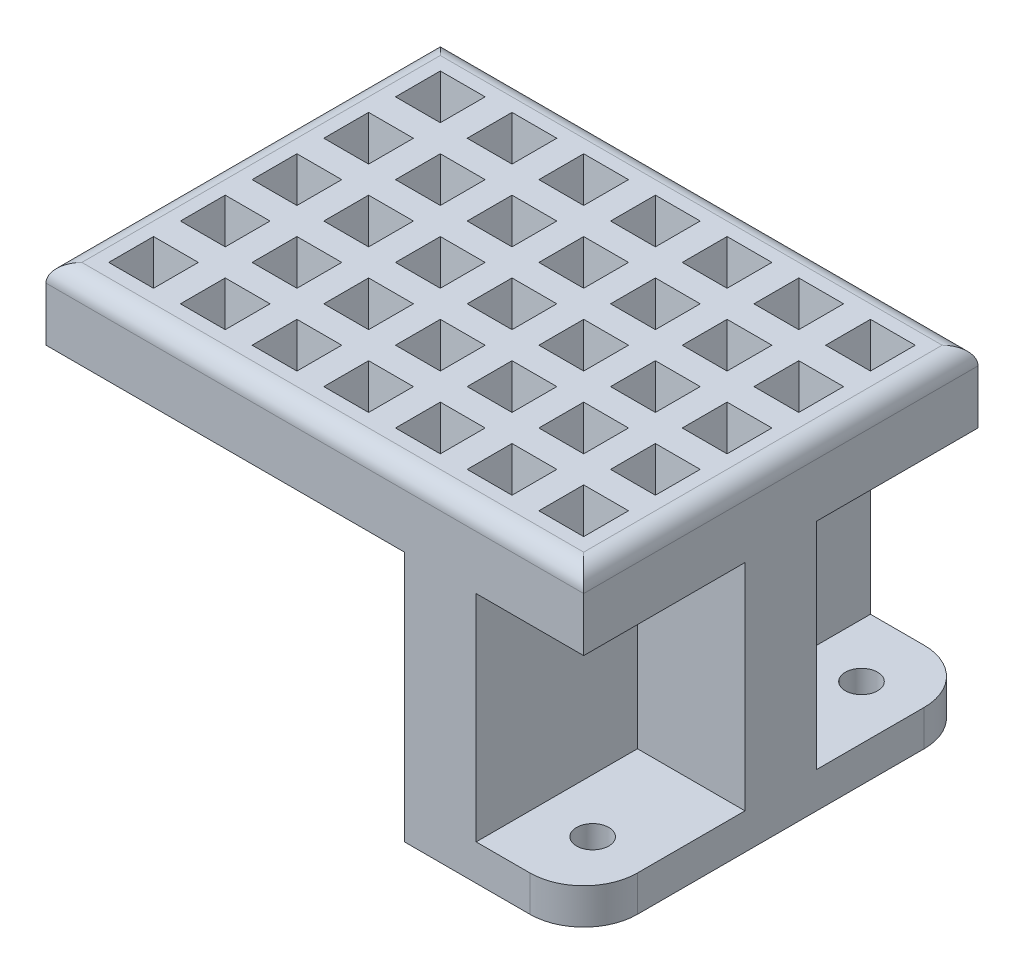
SolidWorks part; units mm, degrees
ref_plane "Спереди" through (0, 0, 0) normal (0, 0, 1) x (1, 0, 0)
ref_plane "Сверху" through (0, 0, 0) normal (0, 1, 0) x (1, 0, 0)
ref_plane "Справа" through (0, 0, 0) normal (1, 0, 0) x (0, 0, -1)
sketch "Эскиз1" plane through (0, 0, 0) normal (0, 1, 0) x (1, 0, 0)
  line L1 (0, -11) -> (-7, -11)
  line L2 (3, -8) -> (3, 8)
  line L3 (0, 11) -> (-7, 11)
  line L4 (-7, -11) -> (-7, 11)
  line L5 (3, -11) -> (-7, 11) construction
  line L6 (3, 11) -> (-7, -11) construction
  circle A0 centre (0, 7.5) radius 0.9
  circle A1 centre (0, -7.5) radius 0.9
  arc A2 (0, -11) -> (3, -8) centre (0, -8) ccw
  arc A3 (3, 8) -> (0, 11) centre (0, 8) ccw
  point P4 (-2, 0)
  dimension "D1" = 1.8
  dimension "D7" = 3
  dimension "D2" = 15
  dimension "D3" = 7.5
  dimension "D4" = 22
  dimension "D5" = 10
  dimension "D6" = 2
extrude "Бобышка-Вытянуть1" add sketch "Эскиз1" along normal blind 2
sketch "Эскиз2" plane through (0, 2, 0) normal (0, 1, 0) x (1, 0, 0)
  line L1 (-3, -11) -> (-7, -11)
  line L2 (-3, -11) -> (-3, -2)
  line L3 (-3, 11) -> (-7, 11)
  line L4 (-7, -11) -> (-7, 11)
  line L5 (-3, -11) -> (-7, 11) construction
  line L6 (-3, 11) -> (-7, -11) construction
  line L7 (-7, 11) -> (-7, -11) construction
  line L8 (-3, 2) -> (-3, 11)
  line L9 (3, -2) -> (-3, -2)
  line L10 (3, -2) -> (3, 2)
  line L11 (3, 2) -> (-3, 2)
  line L13 (3, -2) -> (-3, 2) construction
  line L14 (3, 2) -> (-3, -2) construction
  point P0 (-5, 0)
  point P9 (-7, 0)
  point P10 (0, 0)
  dimension "D1" = 4
  dimension "D2" = 4
extrude "Бобышка-Вытянуть2" add sketch "Эскиз2" along normal blind 12
sketch "Эскиз3" plane through (0, 14, 0) normal (0, 1, 0) x (1, 0, 0)
  line L0 (-7, 11) -> (-7, -11) construction
  line L1 (-27, 11) -> (3, 11)
  line L2 (-27, 11) -> (-27, -11)
  line L3 (-27, -11) -> (3, -11)
  line L4 (3, 11) -> (3, -11)
  line L5 (-27, 11) -> (3, -11) construction
  line L6 (-27, -11) -> (3, 11) construction
  line L8 (3, -2) -> (3, 2) construction
  point P0 (-12, 0)
  point P7 (0, 0)
  point P8 (0, 0)
  dimension "D1" = 30
extrude "Бобышка-Вытянуть3" add sketch "Эскиз3" along normal blind 4
sketch "Эскиз4" plane through (0, 18, 0) normal (0, 1, 0) x (1, 0, 0)
  line L0 (-21.25, 9.25) -> (-21.25, 6.75)
  line L1 (-25.25, 9.25) -> (-22.75, 9.25)
  line L2 (-25.25, 9.25) -> (-25.25, 6.75)
  line L3 (-25.25, 6.75) -> (-22.75, 6.75)
  line L4 (-22.75, 9.25) -> (-22.75, 6.75)
  line L5 (-25.25, 9.25) -> (-22.75, 6.75) construction
  line L6 (-25.25, 6.75) -> (-22.75, 9.25) construction
  line L7 (-21.25, 9.25) -> (-18.75, 9.25)
  line L8 (-18.75, 9.25) -> (-18.75, 6.75)
  line L9 (-21.25, 6.75) -> (-18.75, 6.75)
  line L10 (-17.25, 9.25) -> (-17.25, 6.75)
  line L11 (-17.25, 9.25) -> (-14.75, 9.25)
  line L12 (-14.75, 9.25) -> (-14.75, 6.75)
  line L13 (-17.25, 6.75) -> (-14.75, 6.75)
  line L14 (-13.25, 9.25) -> (-13.25, 6.75)
  line L15 (-13.25, 9.25) -> (-10.75, 9.25)
  line L16 (-10.75, 9.25) -> (-10.75, 6.75)
  line L17 (-13.25, 6.75) -> (-10.75, 6.75)
  line L18 (-9.25, 9.25) -> (-9.25, 6.75)
  line L19 (-9.25, 9.25) -> (-6.75, 9.25)
  line L20 (-6.75, 9.25) -> (-6.75, 6.75)
  line L21 (-9.25, 6.75) -> (-6.75, 6.75)
  line L22 (-5.25, 9.25) -> (-5.25, 6.75)
  line L23 (-5.25, 9.25) -> (-2.75, 9.25)
  line L24 (-2.75, 9.25) -> (-2.75, 6.75)
  line L25 (-5.25, 6.75) -> (-2.75, 6.75)
  line L26 (-1.25, 9.25) -> (-1.25, 6.75)
  line L27 (-1.25, 9.25) -> (1.25, 9.25)
  line L28 (1.25, 9.25) -> (1.25, 6.75)
  line L29 (-1.25, 6.75) -> (1.25, 6.75)
  line L34 (-21.25, 5.25) -> (-21.25, 2.75)
  line L35 (-21.25, 5.25) -> (-18.75, 5.25)
  line L36 (-18.75, 5.25) -> (-18.75, 2.75)
  line L37 (-21.25, 2.75) -> (-18.75, 2.75)
  line L38 (-17.25, 5.25) -> (-17.25, 2.75)
  line L39 (-17.25, 5.25) -> (-14.75, 5.25)
  line L40 (-14.75, 5.25) -> (-14.75, 2.75)
  line L41 (-17.25, 2.75) -> (-14.75, 2.75)
  line L42 (-13.25, 5.25) -> (-13.25, 2.75)
  line L43 (-13.25, 5.25) -> (-10.75, 5.25)
  line L44 (-10.75, 5.25) -> (-10.75, 2.75)
  line L45 (-13.25, 2.75) -> (-10.75, 2.75)
  line L46 (-9.25, 5.25) -> (-9.25, 2.75)
  line L47 (-9.25, 5.25) -> (-6.75, 5.25)
  line L48 (-6.75, 5.25) -> (-6.75, 2.75)
  line L49 (-9.25, 2.75) -> (-6.75, 2.75)
  line L50 (-5.25, 5.25) -> (-5.25, 2.75)
  line L51 (-5.25, 5.25) -> (-2.75, 5.25)
  line L52 (-2.75, 5.25) -> (-2.75, 2.75)
  line L53 (-5.25, 2.75) -> (-2.75, 2.75)
  line L54 (-1.25, 5.25) -> (-1.25, 2.75)
  line L55 (-1.25, 5.25) -> (1.25, 5.25)
  line L56 (1.25, 5.25) -> (1.25, 2.75)
  line L57 (-1.25, 2.75) -> (1.25, 2.75)
  line L62 (-21.25, 1.25) -> (-21.25, -1.25)
  line L63 (-21.25, 1.25) -> (-18.75, 1.25)
  line L64 (-18.75, 1.25) -> (-18.75, -1.25)
  line L65 (-21.25, -1.25) -> (-18.75, -1.25)
  line L66 (-17.25, 1.25) -> (-17.25, -1.25)
  line L67 (-17.25, 1.25) -> (-14.75, 1.25)
  line L68 (-14.75, 1.25) -> (-14.75, -1.25)
  line L69 (-17.25, -1.25) -> (-14.75, -1.25)
  line L70 (-13.25, 1.25) -> (-13.25, -1.25)
  line L71 (-13.25, 1.25) -> (-10.75, 1.25)
  line L72 (-10.75, 1.25) -> (-10.75, -1.25)
  line L73 (-13.25, -1.25) -> (-10.75, -1.25)
  line L74 (-9.25, 1.25) -> (-9.25, -1.25)
  line L75 (-9.25, 1.25) -> (-6.75, 1.25)
  line L76 (-6.75, 1.25) -> (-6.75, -1.25)
  line L77 (-9.25, -1.25) -> (-6.75, -1.25)
  line L78 (-5.25, 1.25) -> (-5.25, -1.25)
  line L79 (-5.25, 1.25) -> (-2.75, 1.25)
  line L80 (-2.75, 1.25) -> (-2.75, -1.25)
  line L81 (-5.25, -1.25) -> (-2.75, -1.25)
  line L82 (-1.25, 1.25) -> (-1.25, -1.25)
  line L83 (-1.25, 1.25) -> (1.25, 1.25)
  line L84 (1.25, 1.25) -> (1.25, -1.25)
  line L85 (-1.25, -1.25) -> (1.25, -1.25)
  line L90 (-21.25, -2.75) -> (-21.25, -5.25)
  line L91 (-21.25, -2.75) -> (-18.75, -2.75)
  line L92 (-18.75, -2.75) -> (-18.75, -5.25)
  line L93 (-21.25, -5.25) -> (-18.75, -5.25)
  line L94 (-17.25, -2.75) -> (-17.25, -5.25)
  line L95 (-17.25, -2.75) -> (-14.75, -2.75)
  line L96 (-14.75, -2.75) -> (-14.75, -5.25)
  line L97 (-17.25, -5.25) -> (-14.75, -5.25)
  line L98 (-13.25, -2.75) -> (-13.25, -5.25)
  line L99 (-13.25, -2.75) -> (-10.75, -2.75)
  line L100 (-10.75, -2.75) -> (-10.75, -5.25)
  line L101 (-13.25, -5.25) -> (-10.75, -5.25)
  line L102 (-9.25, -2.75) -> (-9.25, -5.25)
  line L103 (-9.25, -2.75) -> (-6.75, -2.75)
  line L104 (-6.75, -2.75) -> (-6.75, -5.25)
  line L105 (-9.25, -5.25) -> (-6.75, -5.25)
  line L106 (-5.25, -2.75) -> (-5.25, -5.25)
  line L107 (-5.25, -2.75) -> (-2.75, -2.75)
  line L108 (-2.75, -2.75) -> (-2.75, -5.25)
  line L109 (-5.25, -5.25) -> (-2.75, -5.25)
  line L110 (-1.25, -2.75) -> (-1.25, -5.25)
  line L111 (-1.25, -2.75) -> (1.25, -2.75)
  line L112 (1.25, -2.75) -> (1.25, -5.25)
  line L113 (-1.25, -5.25) -> (1.25, -5.25)
  line L118 (-21.25, -6.75) -> (-21.25, -9.25)
  line L119 (-21.25, -6.75) -> (-18.75, -6.75)
  line L120 (-18.75, -6.75) -> (-18.75, -9.25)
  line L121 (-21.25, -9.25) -> (-18.75, -9.25)
  line L122 (-17.25, -6.75) -> (-17.25, -9.25)
  line L123 (-17.25, -6.75) -> (-14.75, -6.75)
  line L124 (-14.75, -6.75) -> (-14.75, -9.25)
  line L125 (-17.25, -9.25) -> (-14.75, -9.25)
  line L126 (-13.25, -6.75) -> (-13.25, -9.25)
  line L127 (-13.25, -6.75) -> (-10.75, -6.75)
  line L128 (-10.75, -6.75) -> (-10.75, -9.25)
  line L129 (-13.25, -9.25) -> (-10.75, -9.25)
  line L130 (-9.25, -6.75) -> (-9.25, -9.25)
  line L131 (-9.25, -6.75) -> (-6.75, -6.75)
  line L132 (-6.75, -6.75) -> (-6.75, -9.25)
  line L133 (-9.25, -9.25) -> (-6.75, -9.25)
  line L134 (-5.25, -6.75) -> (-5.25, -9.25)
  line L135 (-5.25, -6.75) -> (-2.75, -6.75)
  line L136 (-2.75, -6.75) -> (-2.75, -9.25)
  line L137 (-5.25, -9.25) -> (-2.75, -9.25)
  line L138 (-1.25, -6.75) -> (-1.25, -9.25)
  line L139 (-1.25, -6.75) -> (1.25, -6.75)
  line L140 (1.25, -6.75) -> (1.25, -9.25)
  line L141 (-1.25, -9.25) -> (1.25, -9.25)
  line L146 (-25.25, 5.25) -> (-25.25, 2.75)
  line L147 (-25.25, 5.25) -> (-22.75, 5.25)
  line L148 (-22.75, 5.25) -> (-22.75, 2.75)
  line L149 (-25.25, 2.75) -> (-22.75, 2.75)
  line L150 (-25.25, 1.25) -> (-25.25, -1.25)
  line L151 (-25.25, 1.25) -> (-22.75, 1.25)
  line L152 (-22.75, 1.25) -> (-22.75, -1.25)
  line L153 (-25.25, -1.25) -> (-22.75, -1.25)
  line L154 (-25.25, -2.75) -> (-25.25, -5.25)
  line L155 (-25.25, -2.75) -> (-22.75, -2.75)
  line L156 (-22.75, -2.75) -> (-22.75, -5.25)
  line L157 (-25.25, -5.25) -> (-22.75, -5.25)
  line L158 (-25.25, -6.75) -> (-25.25, -9.25)
  line L159 (-25.25, -6.75) -> (-22.75, -6.75)
  line L160 (-22.75, -6.75) -> (-22.75, -9.25)
  line L161 (-25.25, -9.25) -> (-22.75, -9.25)
  line L162 (-27, 11) -> (-27, -11) construction
  line L163 (3, 11) -> (-27, 11) construction
  point P0 (-24, 8)
  dimension "D1" = 2.5
  dimension "D4" = 1.75
  dimension "D5" = 1.75
extrude "Вырез-Вытянуть1" cut sketch "Эскиз4" against normal blind 3.5 draft 7
fillet "Скругление1" radius 1 4 edges at (3, 18, 0) (-12, 18, -11) (-27, 18, 0) (-12, 18, 11)
equation "\"D3@Эскиз1\"=\"D2@Эскиз1\"/2мм"
